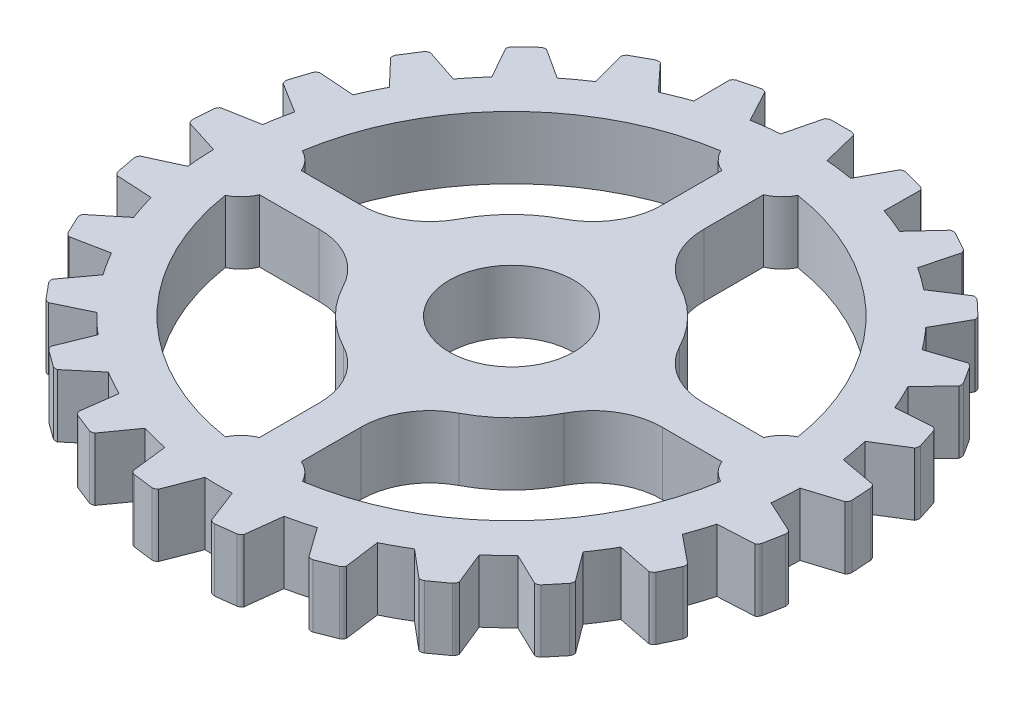
SolidWorks part; units mm, degrees
ref_plane "Płaszczyzna przednia" through (0, 0, 0) normal (0, 0, 1) x (1, 0, 0)
ref_plane "Płaszczyzna górna" through (0, 0, 0) normal (0, 1, 0) x (1, 0, 0)
ref_plane "Płaszczyzna prawa" through (0, 0, 0) normal (1, 0, 0) x (0, 0, -1)
sketch "Szkic1" plane through (0, 0, 0) normal (0, 1, 0) x (1, 0, 0)
  line L0 (0, 0) -> (-101.5385, 0) construction
  line L1 (-50.7692, 0) -> (-50.7692, 21.4103) construction
  line L2 (-40.7692, -81.7421) -> (-40.7692, -110.6563)
  line L3 (-60.7692, -81.7421) -> (-60.7692, -110.6563)
  line L4 (-60.7692, 81.7421) -> (-60.7692, 110.6563)
  line L5 (30.9728, 10) -> (59.8871, 10)
  line L6 (30.9728, -10) -> (59.8871, -10)
  line L7 (-40.7692, 81.7421) -> (-40.7692, 110.6563)
  line L8 (-40.7692, -81.7421) -> (-40.7692, -110.6563)
  line L9 (-60.7692, -81.7421) -> (-60.7692, -110.6563)
  line L10 (-132.5113, -10) -> (-161.4255, -10)
  line L11 (-132.5113, 10) -> (-161.4255, 10)
  line L17 (-5.2421, 132.7701) -> (-5.0995, 150.0252)
  line L18 (-61.8474, 139.921) -> (-57.6944, 156.6694)
  line L19 (-55.6081, 157.8005) -> (-45.9303, 157.8005)
  line L20 (-39.691, 139.921) -> (-43.8441, 156.6694)
  line L21 (-16.2127, 154.0463) -> (-6.839, 151.6395)
  line L22 (-26.7024, 138.2802) -> (-18.5147, 153.4696)
  line L23 (26.3461, 117.2768) -> (30.7754, 133.9543)
  line L24 (21.0114, 140.6128) -> (29.4921, 135.9505)
  line L25 (6.9303, 127.9507) -> (18.6383, 140.6267)
  line L26 (53.089, 94.4145) -> (61.5266, 109.4665)
  line L27 (53.7252, 118.344) -> (60.78, 111.7191)
  line L28 (36.9377, 109.5816) -> (51.4302, 118.9477)
  line L29 (73.306, 65.6198) -> (85.2218, 78.1006)
  line L30 (79.8733, 88.6393) -> (85.0589, 80.4681)
  line L31 (61.434, 84.3271) -> (77.8005, 89.7948)
  line L32 (85.7269, 32.702) -> (100.3723, 41.8273)
  line L33 (97.8126, 53.3651) -> (100.8032, 44.161)
  line L34 (78.8802, 53.774) -> (96.0923, 54.9997)
  line L35 (89.5713, -2.2706) -> (106.0259, 2.9259)
  line L36 (106.416, 14.7377) -> (107.0237, 5.079)
  line L37 (88.1801, 19.842) -> (105.1562, 16.7488)
  line L38 (84.5976, -37.1005) -> (101.8275, -36.1594)
  line L39 (105.1429, -24.8157) -> (103.3294, -34.322)
  line L40 (88.7493, -15.3366) -> (104.4228, -22.5544)
  line L41 (71.1182, -69.5993) -> (88.0409, -72.9727)
  line L42 (94.0732, -62.8098) -> (89.9526, -71.5665)
  line L43 (80.552, -49.5516) -> (93.9381, -60.4405)
  line L44 (49.9803, -97.7249) -> (65.5324, -105.2008)
  line L45 (73.9025, -96.8574) -> (67.7337, -104.3142)
  line L46 (64.1033, -80.6531) -> (74.3609, -94.5289)
  line L47 (22.5118, -119.7101) -> (35.7162, -130.8187)
  line L48 (45.8983, -124.819) -> (38.0688, -130.5075)
  line L49 (40.4367, -106.6869) -> (46.9213, -122.6777)
  line L50 (-9.5611, -134.1734) -> (0.4658, -148.2169)
  line L51 (11.8201, -144.9379) -> (2.8219, -148.5005)
  line L52 (11.0394, -126.0171) -> (13.3435, -143.1182)
  line L53 (-44.2233, -140.2062) -> (-38.0039, -156.302)
  line L54 (-26.1909, -155.9497) -> (-35.7923, -157.1626)
  line L55 (-22.2416, -137.4292) -> (-24.2628, -154.5661)
  line L56 (-79.2968, -137.4292) -> (-77.2757, -154.5661)
  line L57 (-65.7461, -157.1626) -> (-75.3476, -155.9497)
  line L58 (-57.3152, -140.2062) -> (-63.5346, -156.302)
  line L59 (-112.5778, -126.0171) -> (-114.8819, -143.1182)
  line L60 (-104.3604, -148.5005) -> (-113.3585, -144.9379)
  line L61 (-91.9774, -134.1734) -> (-102.0043, -148.2169)
  line L62 (-141.9752, -106.6869) -> (-148.4598, -122.6777)
  line L63 (-139.6073, -130.5075) -> (-147.4368, -124.819)
  line L64 (-124.0503, -119.7101) -> (-137.2547, -130.8187)
  line L65 (-165.6417, -80.6531) -> (-175.8994, -94.5289)
  line L66 (-169.2722, -104.3142) -> (-175.441, -96.8574)
  line L67 (-151.5187, -97.7249) -> (-167.0709, -105.2008)
  line L68 (-182.0904, -49.5516) -> (-195.4766, -60.4405)
  line L69 (-191.4911, -71.5665) -> (-195.6117, -62.8098)
  line L70 (-172.6567, -69.5993) -> (-189.5794, -72.9727)
  line L71 (-190.2877, -15.3366) -> (-205.9613, -22.5544)
  line L72 (-204.8679, -34.322) -> (-206.6813, -24.8157)
  line L73 (-186.136, -37.1005) -> (-203.366, -36.1594)
  line L74 (-189.7185, 19.842) -> (-206.6947, 16.7488)
  line L75 (-208.5622, 5.079) -> (-207.9545, 14.7377)
  line L76 (-191.1098, -2.2706) -> (-207.5644, 2.9259)
  line L77 (-180.4187, 53.774) -> (-197.6307, 54.9997)
  line L78 (-202.3417, 44.161) -> (-199.3511, 53.3651)
  line L79 (-187.2654, 32.702) -> (-201.9107, 41.8273)
  line L80 (-162.9725, 84.3271) -> (-179.3389, 89.7948)
  line L81 (-186.5974, 80.4681) -> (-181.4118, 88.6393)
  line L82 (-174.8444, 65.6198) -> (-186.7603, 78.1006)
  line L83 (-138.4761, 109.5816) -> (-152.9686, 118.9477)
  line L84 (-162.3185, 111.7191) -> (-155.2637, 118.344)
  line L85 (-154.6274, 94.4145) -> (-163.0651, 109.4665)
  line L86 (-108.4688, 127.9507) -> (-120.1768, 140.6267)
  line L87 (-131.0305, 135.9505) -> (-122.5498, 140.6128)
  line L88 (-127.8846, 117.2768) -> (-132.3139, 133.9543)
  line L89 (-74.836, 138.2802) -> (-83.0238, 153.4696)
  line L90 (-94.6995, 151.6395) -> (-85.3257, 154.0463)
  line L91 (-96.2963, 132.7701) -> (-96.4389, 150.0252)
  circle A0 centre (-50.7692, 0) radius 29.81
  arc A1 (-78.3585, 52.8525) -> (-103.6218, 27.5893) centre (-50.7692, 0) ccw
  arc A2 (-69.2125, 118.5742) -> (-169.3434, 18.4433) centre (-50.7692, 0) ccw
  arc A3 (-96.2963, 132.7701) -> (-108.4688, 127.9507) centre (-50.7692, 0) ccw
  arc A4 (-60.7692, 82.1488) -> (-78.4372, 52.8114) centre (-93.6228, 81.9455) cw
  arc A5 (-40.7692, 82.1488) -> (-23.1013, 52.8114) centre (-7.9157, 81.9455) ccw
  arc A6 (-69.2125, 118.5742) -> (-60.7692, 110.6563) centre (-54.3297, 125.9839) ccw
  arc A7 (-32.3259, 118.5742) -> (-40.7692, 110.6563) centre (-47.2088, 125.9839) cw
  arc A8 (-40.7692, -82.1488) -> (-23.1013, -52.8114) centre (-7.9157, -81.9455) cw
  arc A9 (-60.7692, -82.1488) -> (-78.4372, -52.8114) centre (-93.6228, -81.9455) ccw
  arc A10 (-69.2125, -118.5742) -> (-60.7692, -110.6563) centre (-54.3297, -125.9839) cw
  arc A11 (-32.3259, -118.5742) -> (-40.7692, -110.6563) centre (-47.2088, -125.9839) ccw
  arc A12 (-32.3259, -118.5742) -> (67.805, -18.4433) centre (-50.7692, 0) ccw
  arc A13 (-23.18, -52.8525) -> (2.0833, -27.5893) centre (-50.7692, 0) ccw
  circle A14 centre (-50.7692, 0) radius 29.81
  arc A15 (31.3796, -10) -> (2.0422, -27.6679) centre (31.1762, -42.8536) ccw
  arc A16 (31.3796, 10) -> (2.0422, 27.6679) centre (31.1762, 42.8536) cw
  arc A17 (67.805, 18.4433) -> (59.8871, 10) centre (75.2147, 3.5605) ccw
  arc A18 (67.805, -18.4433) -> (59.8871, -10) centre (75.2147, -3.5605) cw
  circle A19 centre (-50.7692, 0) radius 29.81
  arc A20 (-60.7692, -82.1488) -> (-78.4372, -52.8114) centre (-93.6228, -81.9455) ccw
  arc A21 (-40.7692, -82.1488) -> (-23.1013, -52.8114) centre (-7.9157, -81.9455) cw
  arc A22 (-32.3259, -118.5742) -> (-40.7692, -110.6563) centre (-47.2088, -125.9839) ccw
  arc A23 (-69.2125, -118.5742) -> (-60.7692, -110.6563) centre (-54.3297, -125.9839) cw
  circle A24 centre (-50.7692, 0) radius 29.81
  arc A25 (-132.9181, 10) -> (-103.5806, 27.6679) centre (-132.7147, 42.8536) ccw
  arc A26 (-132.9181, -10) -> (-103.5806, -27.6679) centre (-132.7147, -42.8536) cw
  arc A27 (-169.3434, -18.4433) -> (-161.4255, -10) centre (-176.7531, -3.5605) ccw
  arc A28 (-169.3434, 18.4433) -> (-161.4255, 10) centre (-176.7531, 3.5605) cw
  arc A29 (-103.6218, -27.5893) -> (-78.3585, -52.8525) centre (-50.7692, 0) ccw
  arc A30 (2.0833, 27.5893) -> (-23.18, 52.8525) centre (-50.7692, 0) ccw
  arc A31 (-57.6944, 156.6694) -> (-55.6081, 157.8005) centre (-55.1859, 154.5321) cw
  arc A32 (-43.8441, 156.6694) -> (-45.9303, 157.8005) centre (-46.3525, 154.5321) ccw
  arc A33 (-18.5147, 153.4696) -> (-16.2127, 154.0463) centre (-16.6166, 150.7756) cw
  arc A34 (-5.0995, 150.0252) -> (-6.839, 151.6395) centre (-8.0607, 148.5788) ccw
  arc A35 (18.6383, 140.6267) -> (21.0114, 140.6128) centre (19.8068, 137.5453) cw
  arc A36 (30.7754, 133.9543) -> (29.4921, 135.9505) centre (27.5476, 133.2897) ccw
  arc A37 (51.4302, 118.9477) -> (53.7252, 118.344) centre (51.7956, 115.6725) cw
  arc A38 (61.5266, 109.4665) -> (60.78, 111.7191) centre (58.2349, 109.6256) ccw
  arc A39 (77.8005, 89.7948) -> (79.8733, 88.6393) centre (77.3399, 86.5316) cw
  arc A40 (85.2218, 78.1006) -> (85.0589, 80.4681) centre (82.0731, 79.0733) ccw
  arc A41 (96.0923, 54.9997) -> (97.8126, 53.3651) centre (94.8347, 51.9536) cw
  arc A42 (100.3723, 41.8273) -> (100.8032, 44.161) centre (97.5644, 43.5525) ccw
  arc A43 (105.1562, 16.7488) -> (106.416, 14.7377) centre (103.1806, 14.1112) cw
  arc A44 (106.0259, 2.9259) -> (107.0237, 5.079) centre (103.7353, 5.2951) ccw
  arc A45 (104.4228, -22.5544) -> (105.1429, -24.8157) centre (101.8533, -24.6179) cw
  arc A46 (101.8275, -36.1594) -> (103.3294, -34.322) centre (100.1981, -33.2949) ccw
  arc A47 (93.9381, -60.4405) -> (94.0732, -62.8098) centre (90.9361, -61.8002) cw
  arc A48 (88.0409, -72.9727) -> (89.9526, -71.5665) centre (87.175, -69.7929) ccw
  arc A49 (74.3609, -94.5289) -> (73.9025, -96.8574) centre (71.1151, -95.0993) cw
  arc A50 (65.5324, -105.2008) -> (67.7337, -104.3142) centre (65.4845, -101.9056) ccw
  arc A51 (46.9213, -122.6777) -> (45.8983, -124.819) centre (43.6356, -122.423) cw
  arc A52 (35.7162, -130.8187) -> (38.0688, -130.5075) centre (36.4893, -127.6152) ccw
  arc A53 (13.3435, -143.1182) -> (11.8201, -144.9379) centre (10.2244, -142.0544) cw
  arc A54 (0.4658, -148.2169) -> (2.8219, -148.5005) centre (2.0113, -145.3062) ccw
  arc A55 (-24.2628, -154.5661) -> (-26.1909, -155.9497) centre (-27.0193, -152.76) cw
  arc A56 (-38.0039, -156.302) -> (-35.7923, -157.1626) centre (-35.7831, -153.8671) ccw
  arc A57 (-63.5346, -156.302) -> (-65.7461, -157.1626) centre (-65.7553, -153.8671) cw
  arc A58 (-77.2757, -154.5661) -> (-75.3476, -155.9497) centre (-74.5191, -152.76) ccw
  arc A59 (-102.0043, -148.2169) -> (-104.3604, -148.5005) centre (-103.5497, -145.3062) cw
  arc A60 (-114.8819, -143.1182) -> (-113.3585, -144.9379) centre (-111.7628, -142.0544) ccw
  arc A61 (-137.2547, -130.8187) -> (-139.6073, -130.5075) centre (-138.0277, -127.6152) cw
  arc A62 (-148.4598, -122.6777) -> (-147.4368, -124.819) centre (-145.1741, -122.423) ccw
  arc A63 (-167.0709, -105.2008) -> (-169.2722, -104.3142) centre (-167.0229, -101.9056) cw
  arc A64 (-175.8994, -94.5289) -> (-175.441, -96.8574) centre (-172.6536, -95.0993) ccw
  arc A65 (-189.5794, -72.9727) -> (-191.4911, -71.5665) centre (-188.7135, -69.7929) cw
  arc A66 (-195.4766, -60.4405) -> (-195.6117, -62.8098) centre (-192.4746, -61.8002) ccw
  arc A67 (-203.366, -36.1594) -> (-204.8679, -34.322) centre (-201.7365, -33.2949) cw
  arc A68 (-205.9613, -22.5544) -> (-206.6813, -24.8157) centre (-203.3917, -24.6179) ccw
  arc A69 (-207.5644, 2.9259) -> (-208.5622, 5.079) centre (-205.2737, 5.2951) cw
  arc A70 (-206.6947, 16.7488) -> (-207.9545, 14.7377) centre (-204.7191, 14.1112) ccw
  arc A71 (-201.9107, 41.8273) -> (-202.3417, 44.161) centre (-199.1028, 43.5525) cw
  arc A72 (-197.6307, 54.9997) -> (-199.3511, 53.3651) centre (-196.3731, 51.9536) ccw
  arc A73 (-186.7603, 78.1006) -> (-186.5974, 80.4681) centre (-183.6116, 79.0733) cw
  arc A74 (-179.3389, 89.7948) -> (-181.4118, 88.6393) centre (-178.8784, 86.5316) ccw
  arc A75 (-163.0651, 109.4665) -> (-162.3185, 111.7191) centre (-159.7734, 109.6256) cw
  arc A76 (-152.9686, 118.9477) -> (-155.2637, 118.344) centre (-153.3341, 115.6725) ccw
  arc A77 (-132.3139, 133.9543) -> (-131.0305, 135.9505) centre (-129.086, 133.2897) cw
  arc A78 (-120.1768, 140.6267) -> (-122.5498, 140.6128) centre (-121.3452, 137.5453) ccw
  arc A79 (-96.4389, 150.0252) -> (-94.6995, 151.6395) centre (-93.4778, 148.5788) cw
  arc A80 (-83.0238, 153.4696) -> (-85.3257, 154.0463) centre (-84.9218, 150.7756) ccw
  arc A81 (-127.8846, 117.2768) -> (-138.4761, 109.5816) centre (-50.7692, 0) ccw
  arc A82 (-154.6274, 94.4145) -> (-162.9725, 84.3271) centre (-50.7692, 0) ccw
  arc A83 (-174.8444, 65.6198) -> (-180.4187, 53.774) centre (-50.7692, 0) ccw
  arc A84 (-187.2654, 32.702) -> (-189.7185, 19.842) centre (-50.7692, 0) ccw
  arc A85 (-191.1098, -2.2706) -> (-190.2877, -15.3366) centre (-50.7692, 0) ccw
  arc A86 (-186.136, -37.1005) -> (-182.0904, -49.5516) centre (-50.7692, 0) ccw
  arc A87 (-172.6567, -69.5993) -> (-165.6417, -80.6531) centre (-50.7692, 0) ccw
  arc A88 (-151.5187, -97.7249) -> (-141.9752, -106.6869) centre (-50.7692, 0) ccw
  arc A89 (-124.0503, -119.7101) -> (-112.5778, -126.0171) centre (-50.7692, 0) ccw
  arc A90 (-91.9774, -134.1734) -> (-79.2968, -137.4292) centre (-50.7692, 0) ccw
  arc A91 (-57.3152, -140.2062) -> (-44.2233, -140.2062) centre (-50.7692, 0) ccw
  arc A92 (-22.2416, -137.4292) -> (-9.5611, -134.1734) centre (-50.7692, 0) ccw
  arc A93 (11.0394, -126.0171) -> (22.5118, -119.7101) centre (-50.7692, 0) ccw
  arc A94 (40.4367, -106.6869) -> (49.9803, -97.7249) centre (-50.7692, 0) ccw
  arc A95 (64.1033, -80.6531) -> (71.1182, -69.5993) centre (-50.7692, 0) ccw
  arc A96 (80.552, -49.5516) -> (84.5976, -37.1005) centre (-50.7692, 0) ccw
  arc A97 (88.7493, -15.3366) -> (89.5713, -2.2706) centre (-50.7692, 0) ccw
  arc A98 (88.1801, 19.842) -> (85.7269, 32.702) centre (-50.7692, 0) ccw
  arc A99 (78.8802, 53.774) -> (73.306, 65.6198) centre (-50.7692, 0) ccw
  arc A100 (61.434, 84.3271) -> (53.089, 94.4145) centre (-50.7692, 0) ccw
  arc A101 (36.9377, 109.5816) -> (26.3461, 117.2768) centre (-50.7692, 0) ccw
  arc A102 (6.9303, 127.9507) -> (-5.2421, 132.7701) centre (-50.7692, 0) ccw
  arc A103 (-26.7024, 138.2802) -> (-39.691, 139.921) centre (-50.7692, 0) ccw
  arc A104 (-61.8474, 139.921) -> (-74.836, 138.2802) centre (-50.7692, 0) ccw
  arc A105 (67.805, 18.4433) -> (-32.3259, 118.5742) centre (-50.7692, 0) ccw
  arc A106 (-169.3434, -18.4433) -> (-69.2125, -118.5742) centre (-50.7692, 0) ccw
  point P12 (-50.7692, 44.7151)
  point P15 (-243.0769, 136.5385)
  point P89 (-50.7692, 0)
  point P90 (-50.7692, 140)
  point P91 (-49.518, 136.5385)
  point P92 (-50.7692, 134.0817)
  point P93 (-50.7692, 134.0817)
  point P99 (-50.7692, 157.8005)
  dimension "D1" = 4
  dimension "D2" = 25
extrude "Dodanie-wyciągnięcie2" add sketch "Szkic1" along normal blind 30 contours L18 A104 L89 A80 L90 A79 L91 A3 L86 A78 L87 A77 L88 A81 L83 A76 L84 A75 L85 A82 L80 A74 L81 A73 L82 A83 L77 A72 L78 A71 L79 A84 L74 A70 L75 A69 L76 A85 L71 A68 L72 A67 L73 A86 L68 A66 L69 A65 L70 A87 L65
